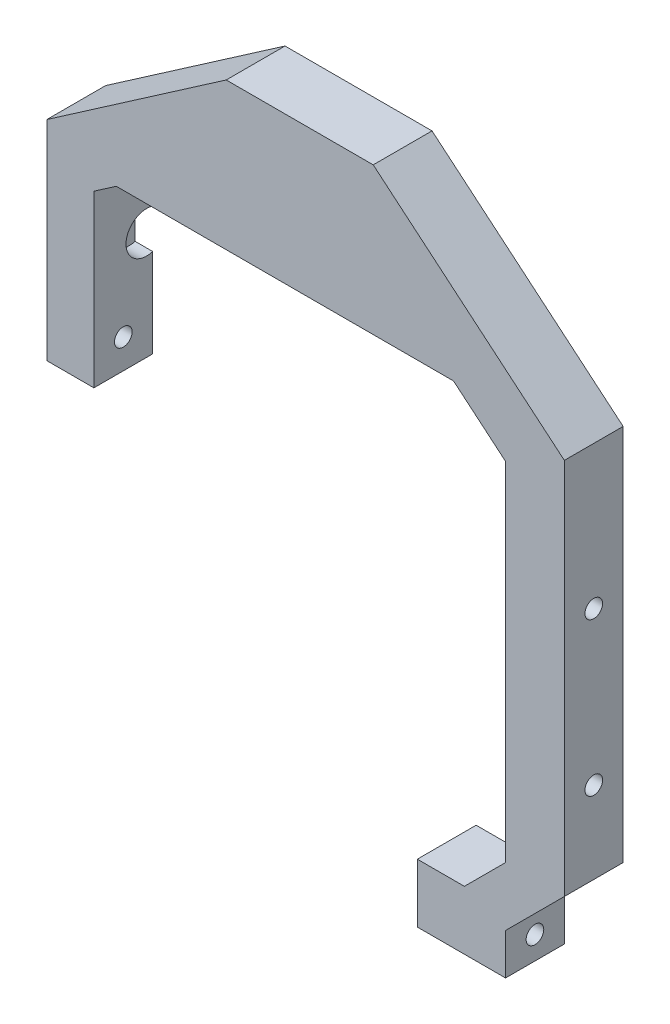
SolidWorks part; units mm, degrees
ref_plane "Front Plane" through (0, 0, 0) normal (0, 0, 1) x (1, 0, 0)
ref_plane "Top Plane" through (0, 0, 0) normal (0, 1, 0) x (1, 0, 0)
ref_plane "Right Plane" through (0, 0, 0) normal (1, 0, 0) x (0, 0, -1)
sketch "Sketch1" plane through (0, 0, 0) normal (0, 0, 1) x (-1, 0, 0)
  line L0 (47.5, 51.3406) -> (47.5, 46.0403) construction
  line L1 (47.5, 36.6421) -> (47.5, 56.5937)
  line L2 (47.5, 56.5937) -> (55.5, 56.5937)
  line L3 (55.5, 56.5937) -> (55.5, 30.5)
  line L4 (55.5, 21.0769) -> (25, 0)
  line L5 (25, 0) -> (0, 0)
  line L7 (-13.6614, 25) -> (-22.5, 32.4165)
  line L8 (-32.5, 40.5) -> (-32.5, 108.5)
  line L9 (0, 0) -> (-32.5, 27.2707)
  line L10 (-32.5, 108.5) -> (-7.5, 108.5)
  line L11 (-22.5, 98.5) -> (-7.5, 98.5)
  line L12 (-32.5, 27.2707) -> (-32.5, 40.5)
  line L14 (-22.5, 98.5) -> (-22.5, 32.4165)
  line L15 (55.5, 21.0769) -> (55.5, 30.5)
  line L16 (-13.6614, 25) -> (35.8579, 25)
  line L17 (35.8579, 25) -> (43.6903, 25)
  line L18 (-7.5, 98.5) -> (-7.5, 108.5)
  line L19 (43.6903, 25) -> (47.5, 27.6327)
  line L20 (47.5, 27.6327) -> (47.5, 36.6421)
  dimension "D1" = 68
  dimension "D2" = 8
  dimension "D3" = 10
  dimension "D4" = 10
  dimension "D5" = 25
  dimension "D7" = 26.0937
  dimension "D8" = 25
  dimension "D9" = 40
  dimension "D12" = 25
  dimension "D13" = 56.5937
  dimension "D14" = 108.5
  dimension "D15" = 70
extrude "Boss-Extrude1" add sketch "Sketch1" along normal blind 10
sketch "Sketch2" plane through (-55.5, 0, 0) normal (-1, 0, 0) x (0, 0, 1)
  line L0 (10, -56.5937) -> (0, -56.5937) construction
  line L1 (10, -21.0769) -> (10, -56.5937) construction
  circle A0 centre (5, -51.5937) radius 1.5
  dimension "D3" = 3
  dimension "D1" = 5
  dimension "D2" = 5
extrude "Cut-Extrude1" cut sketch "Sketch2" against normal through all
sketch "Sketch3" plane through (32.5, 0, 0) normal (1, 0, 0) x (0, 0, -1)
  line L0 (0, -108.5) -> (0, -27.2707) construction
  circle A0 centre (-5, -77.5937) radius 1.5
  circle A1 centre (-5, -51.5937) radius 1.5 construction
  dimension "D1" = 26
  dimension "D2" = 3
  dimension "D3" = 5
extrude "Cut-Extrude2" cut sketch "Sketch3" against normal up to next
chamfer "Chamfer2" distance 7 angle 45 1 edges at (22.5, -98.5, 5)
sketch "Sketch4" plane through (0, 0, 10) normal (0, 0, 1) x (1, 0, 0)
  line L0 (22.5, -108.5) -> (22.5, -101.5)
  line L2 (22.5, -101.5) -> (32.5, -91.5)
  line L3 (32.5, -108.5) -> (32.5, -27.2707) construction
  line L4 (22.5, -32.4165) -> (22.5, -91.5) construction
  line L5 (7.5, -108.5) -> (32.5, -108.5) construction
  line L6 (22.5, -108.5) -> (32.5, -108.5)
  line L7 (32.5, -108.5) -> (32.5, -91.5)
  dimension "D1" = 7
  dimension "D2" = 45
extrude "Cut-Extrude3" cut sketch "Sketch4" against normal up to next
sketch "Sketch5" plane through (22.5, 0, 0) normal (1, 0, 0) x (0, 0, -1)
  line L2 (-10, -101.5) -> (-10, -108.5) construction
  circle A0 centre (-5, -104.5937) radius 1.5
  dimension "D1" = 5
  dimension "D3" = 3
  dimension "D2" = 27
extrude "Cut-Extrude4" cut sketch "Sketch5" against normal up to next
sketch "Sketch9" plane through (-47.5, 0, 0) normal (1, 0, 0) x (0, 0, -1)
  line L0 (-10, -56.5937) -> (0, -56.5937) construction
  line L1 (0, -56.5937) -> (0, -27.6327) construction
  circle A0 centre (-1.0362, -38.1666) radius 3.5
  dimension "D1" = 7
  dimension "D2" = 18.4271
  dimension "D3" = 1.0362
extrude "Cut-Extrude7" cut sketch "Sketch9" against normal blind 3
sketch "Sketch10" plane through (22.5, 0, 0) normal (-1, 0, 0) x (0, 0, 1)
  line L0 (10, -32.4165) -> (0, -32.4165) construction
  line L1 (0, -32.4165) -> (0, -91.5) construction
  circle A0 centre (1.0362, -38.1666) radius 3.5
  circle A1 centre (1.0362, -64.1666) radius 3.5
  dimension "D1" = 7
  dimension "D2" = 5.7501
  dimension "D3" = 26
  dimension "D4" = 1.0362
extrude "Cut-Extrude8" cut sketch "Sketch10" against normal blind 3
